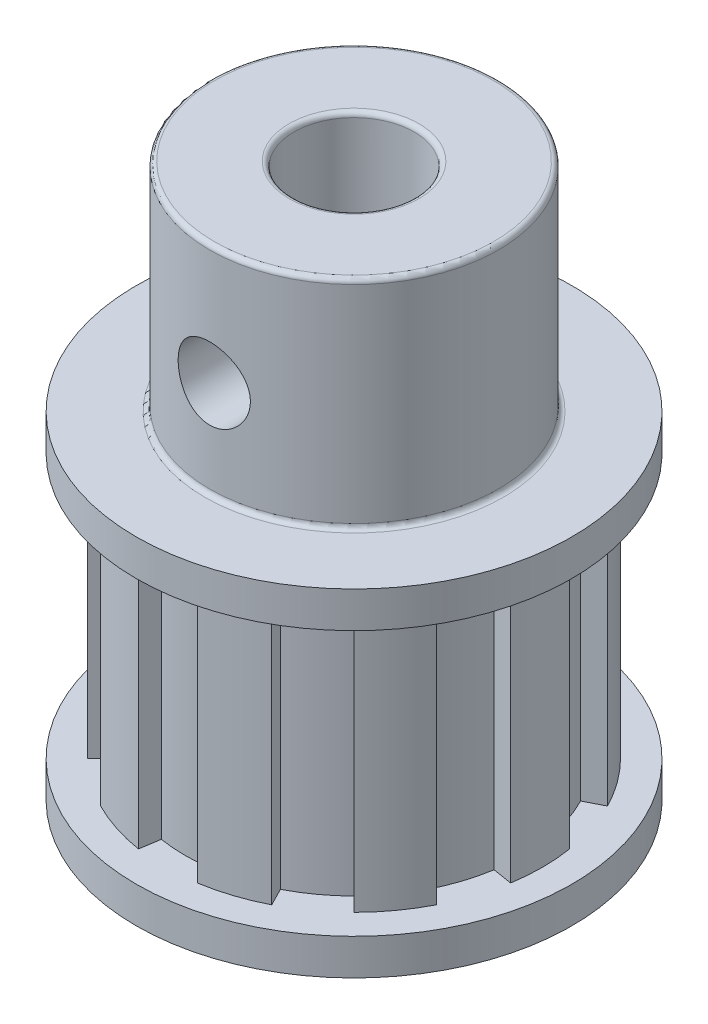
SolidWorks part; units mm, degrees
ref_plane "Front Plane" through (0, 0, 0) normal (0, 0, 1) x (1, 0, 0)
ref_plane "Top Plane" through (0, 0, 0) normal (0, 1, 0) x (1, 0, 0)
ref_plane "Right Plane" through (0, 0, 0) normal (1, 0, 0) x (0, 0, -1)
sketch "Sketch1" plane through (0, 0, 0) normal (0, 1, 0) x (1, 0, 0)
  circle A0 centre (0, 0) radius 9.05
  dimension "D1" = 18.1
extrude "Boss-Extrude1" add sketch "Sketch1" along normal blind 1.5
sketch "Sketch2" plane through (0, 1.5, 0) normal (0, 1, 0) x (1, 0, 0)
  circle A0 centre (0, 0) radius 7.83
  dimension "D1" = 15.66
extrude "Boss-Extrude2" add sketch "Sketch2" along normal blind 11
sketch "Sketch4" plane through (0, 12.5, 0) normal (0, 1, 0) x (1, 0, 0)
  line L0 (0, 7.83) -> (0, -7.83) construction
  line L1 (-1.095, 6.9138) -> (-1.2249, 7.7336)
  line L2 (1.095, 6.9138) -> (1.2249, 7.7336)
  line L3 (3.1779, 6.237) -> (3.5547, 6.9766)
  line L4 (4.9497, 4.9497) -> (5.5366, 5.5366)
  line L5 (6.237, 3.1779) -> (6.9766, 3.5547)
  line L6 (6.9138, 1.095) -> (7.7336, 1.2249)
  line L7 (6.9138, -1.095) -> (7.7336, -1.2249)
  line L8 (6.237, -3.1779) -> (6.9766, -3.5547)
  line L9 (4.9497, -4.9497) -> (5.5366, -5.5366)
  line L10 (3.1779, -6.237) -> (3.5547, -6.9766)
  line L11 (1.095, -6.9138) -> (1.2249, -7.7336)
  line L12 (-1.095, -6.9138) -> (-1.2249, -7.7336)
  line L13 (-3.1779, -6.237) -> (-3.5547, -6.9766)
  line L14 (-4.9497, -4.9497) -> (-5.5366, -5.5366)
  line L15 (-6.237, -3.1779) -> (-6.9766, -3.5547)
  line L16 (-6.9138, -1.095) -> (-7.7336, -1.2249)
  line L17 (-6.9138, 1.095) -> (-7.7336, 1.2249)
  line L18 (-6.237, 3.1779) -> (-6.9766, 3.5547)
  line L19 (-4.9497, 4.9497) -> (-5.5366, 5.5366)
  line L20 (-3.1779, 6.237) -> (-3.5547, 6.9766)
  arc A0 (1.095, 6.9138) -> (-1.095, 6.9138) centre (0, 0) ccw
  circle A1 centre (0, 0) radius 7.83 construction
  circle A2 centre (0, 0) radius 7.83 construction
  arc A3 (1.2249, 7.7336) -> (-1.2249, 7.7336) centre (0, 0) ccw
  arc A4 (5.5366, 5.5366) -> (3.5547, 6.9766) centre (0, 0) ccw
  arc A5 (4.9497, 4.9497) -> (3.1779, 6.237) centre (0, 0) ccw
  arc A6 (7.7336, 1.2249) -> (6.9766, 3.5547) centre (0, 0) ccw
  arc A7 (6.9138, 1.095) -> (6.237, 3.1779) centre (0, 0) ccw
  arc A8 (6.9766, -3.5547) -> (7.7336, -1.2249) centre (0, 0) ccw
  arc A9 (6.237, -3.1779) -> (6.9138, -1.095) centre (0, 0) ccw
  arc A10 (3.5547, -6.9766) -> (5.5366, -5.5366) centre (0, 0) ccw
  arc A11 (3.1779, -6.237) -> (4.9497, -4.9497) centre (0, 0) ccw
  arc A12 (-1.2249, -7.7336) -> (1.2249, -7.7336) centre (0, 0) ccw
  arc A13 (-1.095, -6.9138) -> (1.095, -6.9138) centre (0, 0) ccw
  arc A14 (-5.5366, -5.5366) -> (-3.5547, -6.9766) centre (0, 0) ccw
  arc A15 (-4.9497, -4.9497) -> (-3.1779, -6.237) centre (0, 0) ccw
  arc A16 (-7.7336, -1.2249) -> (-6.9766, -3.5547) centre (0, 0) ccw
  arc A17 (-6.9138, -1.095) -> (-6.237, -3.1779) centre (0, 0) ccw
  arc A18 (-6.9766, 3.5547) -> (-7.7336, 1.2249) centre (0, 0) ccw
  arc A19 (-6.237, 3.1779) -> (-6.9138, 1.095) centre (0, 0) ccw
  arc A20 (-3.5547, 6.9766) -> (-5.5366, 5.5366) centre (0, 0) ccw
  arc A21 (-3.1779, 6.237) -> (-4.9497, 4.9497) centre (0, 0) ccw
  point P52 (0, 0)
  dimension "D1" = 14
  dimension "D2" = 9
  dimension "D3" = 10
extrude "Cut-Extrude1" cut sketch "Sketch4" against normal up to surface (11 mm away) up to face at (0, 1.5, 7.83)
sketch "Sketch3" plane through (0, 12.5, 0) normal (0, 1, 0) x (1, 0, 0)
  circle A0 centre (0, 0) radius 9.05
extrude "Boss-Extrude3" add sketch "Sketch3" along normal blind 1.5
sketch "Sketch5" plane through (0, 14, 0) normal (0, 1, 0) x (1, 0, 0)
  circle A0 centre (0, 0) radius 6
  dimension "D1" = 12
extrude "Boss-Extrude4" add sketch "Sketch5" along normal blind 9
sketch "Sketch6" plane through (0, 23, 0) normal (0, 1, 0) x (1, 0, 0)
  circle A0 centre (0, 0) radius 2.5
  dimension "D1" = 5
extrude "Cut-Extrude2" cut sketch "Sketch6" against normal through all
sketch "Sketch7" plane through (0, 0, 0) normal (0, 0, 1) x (1, 0, 0)
  line L0 (0, 23.459) -> (0, -1.3828) construction
  circle A0 centre (0, 18) radius 1.5
  dimension "D2" = 3
  dimension "D1" = 18
extrude "Cut-Extrude3" cut sketch "Sketch7" against normal through all both and the other way through all
fillet "Fillet1" radius 0.2 4 edges at (0, 0, 2.5) (0, 23, 2.5) (0, 23, 6) (0, 14, 6)
